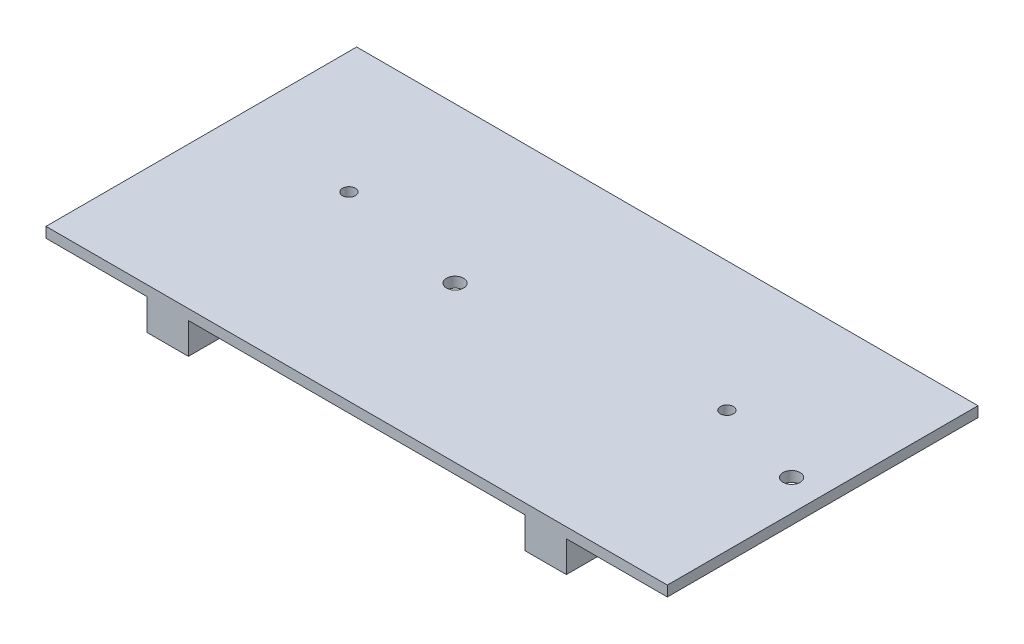
SolidWorks part; units mm, degrees
ref_plane "前视基准面" through (0, 0, 0) normal (0, 0, 1) x (1, 0, 0)
ref_plane "上视基准面" through (0, 0, 0) normal (0, 1, 0) x (1, 0, 0)
ref_plane "右视基准面" through (0, 0, 0) normal (1, 0, 0) x (0, 0, -1)
sketch "草图1" plane through (0, 0, 0) normal (0, 1, 0) x (1, 0, 0)
  line L1 (60, -30) -> (-60, -30)
  line L2 (60, -30) -> (60, 30)
  line L3 (60, 30) -> (-60, 30)
  line L4 (-60, -30) -> (-60, 30)
  line L5 (60, -30) -> (-60, 30) construction
  line L6 (60, 30) -> (-60, -30) construction
  point P0 (0, 0)
  dimension "D1" = 120
  dimension "D2" = 60
extrude "凸台-拉伸1" add sketch "草图1" along normal blind 2
sketch "草图2" plane through (0, 0, 0) normal (0, -1, 0) x (1, 0, 0)
  line L0 (-60, 30) -> (60, 30) construction
  line L1 (-40.5, 30) -> (-32.5, 30)
  line L2 (-40.5, 30) -> (-40.5, -30)
  line L3 (-40.5, -30) -> (-32.5, -30)
  line L4 (-32.5, 30) -> (-32.5, -30)
  line L5 (60, -30) -> (-60, -30) construction
  line L7 (0, 0) -> (0, 30) construction
  line L8 (32.5, 30) -> (32.5, -30)
  line L9 (40.5, -30) -> (32.5, -30)
  line L10 (40.5, 30) -> (40.5, -30)
  line L11 (40.5, 30) -> (32.5, 30)
  line L12 (-36.5, 30) -> (-36.5, 14.3664) construction
  dimension "D1" = 36.5
  dimension "D2" = 8
extrude "凸台-拉伸2" add sketch "草图2" along normal blind 6
hole_wizard "M3 螺纹孔1" positions "草图3" profile "草图4" tap size "M3" standard "GB"
sketch "草图3" plane through (0, -6, 0) normal (0, -1, 0) x (-1, 0, 0)
  line L0 (0, 0) -> (0, -30) construction
  line L1 (32.5, -30) -> (-32.5, -30) construction
  line L3 (32.5, -30) -> (40.5, -30) construction
  line L4 (-32.5, 30) -> (32.5, 30) construction
  point P0 (36.5, 5)
  point P2 (-36.5, 5)
  point P13 (36.5, -30)
  dimension "D1" = 25
sketch "草图4" plane through (-36.5, -6, -5) normal (1, 0, 0) x (0, 0, -1)
  line L0 (0, 0) -> (0, 9.2511)
  line L1 (0, 9.2511) -> (1.25, 8.5)
  line L2 (1.25, 8.5) -> (1.25, 0)
  line L5 (1.25, 0) -> (0, 0)
  line L10 (0, 9.2511) -> (-1.25, 8.5) construction
  line L11 (0, -6.35) -> (0, 107.95) construction
  dimension "螺纹孔钻头直径" = 2.5
  dimension "螺纹孔钻头深度" = 8.5
  dimension "导头角度" = 118
cosmetic thread "孔螺蚊线1" parameters "D1"=6, "D2"=3
cosmetic thread "孔螺蚊线2" parameters "D1"=6, "D2"=3
hole_wizard "M4 螺纹孔1" positions "草图5" profile "草图6" tap size "M4" standard "GB" end condition through all
sketch "草图5" plane through (0, 2, 0) normal (0, 1, 0) x (1, 0, 0)
  line L0 (60, 30) -> (-60, 30) construction
  line L1 (60, -30) -> (60, 30) construction
  point P0 (54, 0)
  point P2 (-11, 0)
  dimension "D1" = 30
  dimension "D2" = 65
  dimension "D3" = 6
sketch "草图6" plane through (54, 2, 0) normal (1, 0, 0) x (0, 0, 1)
  line L0 (0, 0) -> (0, 8)
  line L1 (0, 8) -> (1.65, 8)
  line L2 (1.65, 8) -> (1.65, 0)
  line L5 (1.65, 0) -> (0, 0)
  line L11 (0, -6.35) -> (0, 107.95) construction
  dimension "通孔螺纹孔钻头直径" = 3.3
  dimension "通孔螺纹孔钻头深度" = 8
cosmetic thread "孔螺蚊线3" parameters "D2"=4
cosmetic thread "孔螺蚊线4" parameters "D2"=4
